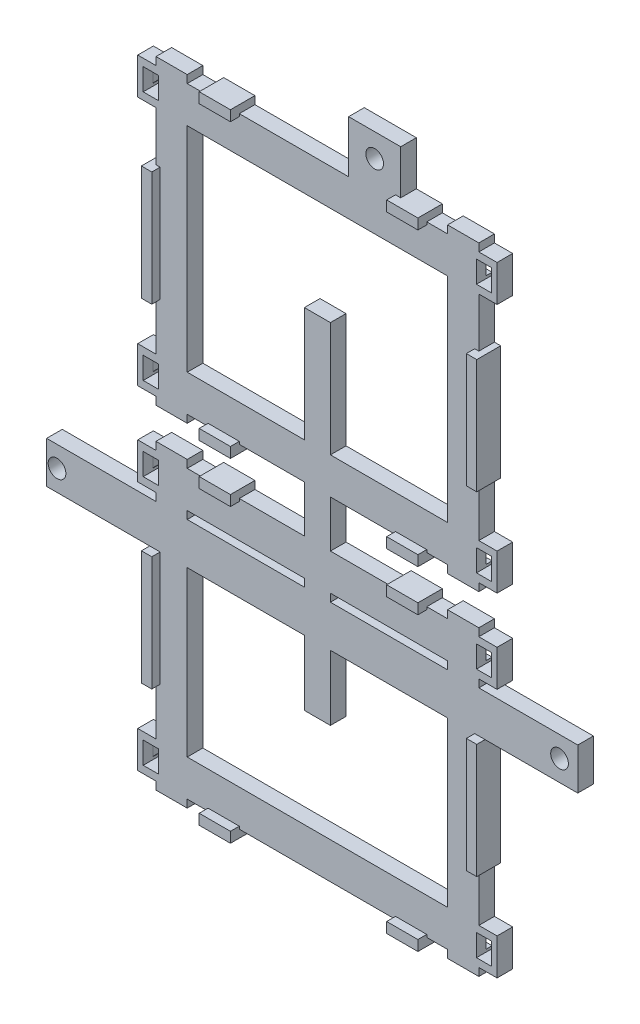
SolidWorks part; units mm, degrees
ref_plane "前视基准面" through (0, 0, 0) normal (0, 0, 1) x (1, 0, 0)
ref_plane "上视基准面" through (0, 0, 0) normal (0, 1, 0) x (1, 0, 0)
ref_plane "右视基准面" through (0, 0, 0) normal (1, 0, 0) x (0, 0, -1)
other "Configuration Table"
sketch "Sketch_Connected_support_rails" plane through (0, 0, 0) normal (0, 0, 1) x (1, 0, 0)
  line L0 (-25, -59.5) -> (-25, -61)
  line L1 (-25, -61) -> (-31, -61)
  line L2 (-31, -61) -> (-31, -59.5)
  line L3 (-31, -59.5) -> (-34.5, -59.5)
  line L4 (-34.5, -59.5) -> (-34.5, -52.5)
  line L5 (-34.5, -52.5) -> (-31, -52.5)
  line L6 (-31, -52.5) -> (-31, -43)
  line L7 (-31, -43) -> (-32.2, -43)
  line L8 (-32.2, -43) -> (-32.2, -21)
  line L9 (-32.2, -21) -> (-52, -21)
  line L10 (-52, -21) -> (-52, -13)
  line L11 (-52, -13) -> (-31, -13)
  line L12 (-31, -13) -> (-31, -11.5)
  line L13 (-31, -11.5) -> (-34.5, -11.5)
  line L14 (-34.5, -11.5) -> (-34.5, -4.5)
  line L15 (-34.5, -4.5) -> (-31, -4.5)
  line L16 (-31, -4.5) -> (-31, -3)
  line L17 (-31, -3) -> (-25, -3)
  line L18 (-25, -3) -> (-25, -4.5)
  line L19 (-25, -4.5) -> (-21, -4.5)
  line L20 (-21, -4.5) -> (-21, -3)
  line L21 (-21, -3) -> (-15, -3)
  line L22 (-15, -3) -> (-15, -4.5)
  line L23 (-15, -4.5) -> (-2.5, -4.5)
  line L24 (-2.5, -4.5) -> (-2.5, 4.5)
  line L25 (-2.5, 4.5) -> (-15, 4.5)
  line L26 (-15, 4.5) -> (-15, 3)
  line L27 (-15, 3) -> (-21, 3)
  line L28 (-21, 3) -> (-21, 4.5)
  line L29 (-21, 4.5) -> (-25, 4.5)
  line L30 (-25, 4.5) -> (-25, 3)
  line L31 (-25, 3) -> (-31, 3)
  line L32 (-31, 3) -> (-31, 4.5)
  line L33 (-31, 4.5) -> (-34.5, 4.5)
  line L34 (-34.5, 4.5) -> (-34.5, 11.5)
  line L35 (-34.5, 11.5) -> (-31, 11.5)
  line L36 (-31, 11.5) -> (-31, 21)
  line L37 (-31, 21) -> (-32.2, 21)
  line L38 (-32.2, 21) -> (-32.2, 43)
  line L39 (-32.2, 43) -> (-31, 43)
  line L40 (-31, 43) -> (-31, 52.5)
  line L41 (-31, 52.5) -> (-34.5, 52.5)
  line L42 (-34.5, 52.5) -> (-34.5, 59.5)
  line L43 (-34.5, 59.5) -> (-31, 59.5)
  line L44 (-31, 59.5) -> (-31, 61)
  line L45 (-31, 61) -> (-25, 61)
  line L46 (-25, 61) -> (-25, 59.5)
  line L47 (-25, 59.5) -> (-21, 59.5)
  line L48 (-21, 59.5) -> (-21, 61)
  line L49 (-21, 61) -> (-15, 61)
  line L50 (-15, 61) -> (-15, 59.5)
  line L51 (-15, 59.5) -> (6, 59.5)
  line L52 (6, 59.5) -> (6, 69.5)
  line L53 (6, 69.5) -> (16, 69.5)
  line L54 (16, 69.5) -> (16, 61)
  line L55 (16, 61) -> (21, 61)
  line L56 (21, 61) -> (21, 59.5)
  line L57 (21, 59.5) -> (25, 59.5)
  line L58 (25, 59.5) -> (25, 61)
  line L59 (25, 61) -> (31, 61)
  line L60 (31, 61) -> (31, 59.5)
  line L61 (31, 59.5) -> (34.5, 59.5)
  line L62 (34.5, 59.5) -> (34.5, 52.5)
  line L63 (34.5, 52.5) -> (31, 52.5)
  line L64 (31, 52.5) -> (31, 43)
  line L65 (31, 43) -> (32.2, 43)
  line L66 (32.2, 43) -> (32.2, 21)
  line L67 (32.2, 21) -> (31, 21)
  line L68 (31, 21) -> (31, 11.5)
  line L69 (31, 11.5) -> (34.5, 11.5)
  line L70 (34.5, 11.5) -> (34.5, 4.5)
  line L71 (34.5, 4.5) -> (31, 4.5)
  line L72 (31, 4.5) -> (31, 3)
  line L73 (31, 3) -> (25, 3)
  line L74 (25, 3) -> (25, 4.5)
  line L75 (25, 4.5) -> (21, 4.5)
  line L76 (21, 4.5) -> (21, 3)
  line L77 (21, 3) -> (15, 3)
  line L78 (15, 3) -> (15, 4.5)
  line L79 (15, 4.5) -> (2.5, 4.5)
  line L80 (2.5, 4.5) -> (2.5, -4.5)
  line L81 (2.5, -4.5) -> (15, -4.5)
  line L82 (15, -4.5) -> (15, -3)
  line L83 (15, -3) -> (21, -3)
  line L84 (21, -3) -> (21, -4.5)
  line L85 (21, -4.5) -> (25, -4.5)
  line L86 (25, -4.5) -> (25, -3)
  line L87 (25, -3) -> (31, -3)
  line L88 (31, -3) -> (31, -4.5)
  line L89 (31, -4.5) -> (34.5, -4.5)
  line L90 (34.5, -4.5) -> (34.5, -11.5)
  line L91 (34.5, -11.5) -> (31, -11.5)
  line L92 (31, -11.5) -> (31, -13)
  line L93 (31, -13) -> (50, -13)
  line L94 (50, -13) -> (50, -21)
  line L95 (50, -21) -> (32.2, -21)
  line L96 (32.2, -21) -> (32.2, -43)
  line L97 (32.2, -43) -> (31, -43)
  line L98 (31, -43) -> (31, -52.5)
  line L99 (31, -52.5) -> (34.5, -52.5)
  line L100 (34.5, -52.5) -> (34.5, -59.5)
  line L101 (34.5, -59.5) -> (31, -59.5)
  line L102 (31, -59.5) -> (31, -61)
  line L103 (31, -61) -> (25, -61)
  line L104 (25, -61) -> (25, -59.5)
  line L105 (25, -59.5) -> (21, -59.5)
  line L106 (21, -59.5) -> (21, -61)
  line L107 (21, -61) -> (15, -61)
  line L108 (15, -61) -> (15, -59.5)
  line L109 (15, -59.5) -> (-15, -59.5)
  line L110 (-15, -59.5) -> (-15, -61)
  line L111 (-15, -61) -> (-21, -61)
  line L112 (-21, -61) -> (-21, -59.5)
  line L113 (-21, -59.5) -> (-25, -59.5)
  line L114 (2.5, -11.5) -> (2.5, -13)
  line L115 (2.5, -13) -> (25, -13)
  line L116 (25, -13) -> (25, -11.5)
  line L117 (25, -11.5) -> (2.5, -11.5)
  line L118 (-25, -11.5) -> (-25, -13)
  line L119 (-25, -13) -> (-2.5, -13)
  line L120 (-2.5, -13) -> (-2.5, -11.5)
  line L121 (-2.5, -11.5) -> (-25, -11.5)
  line L122 (2.5, -21) -> (2.5, -33.5)
  line L123 (2.5, -33.5) -> (-2.5, -33.5)
  line L124 (-2.5, -33.5) -> (-2.5, -21)
  line L125 (-2.5, -21) -> (-25, -21)
  line L126 (-25, -21) -> (-25, -52.5)
  line L127 (-25, -52.5) -> (25, -52.5)
  line L128 (25, -52.5) -> (25, -21)
  line L129 (25, -21) -> (2.5, -21)
  line L130 (-25, 11.5) -> (-2.5, 11.5)
  line L131 (-2.5, 11.5) -> (-2.5, 33.5)
  line L132 (-2.5, 33.5) -> (2.5, 33.5)
  line L133 (2.5, 33.5) -> (2.5, 11.5)
  line L134 (2.5, 11.5) -> (25, 11.5)
  line L135 (25, 11.5) -> (25, 52.5)
  line L136 (25, 52.5) -> (-25, 52.5)
  line L137 (-25, 52.5) -> (-25, 11.5)
extrude "Connected_support_rails" add sketch "Sketch_Connected_support_rails" along normal blind 3 from offset 0
sketch "Sketch_Side_stops" plane through (0, 0, 0) normal (0, 0, 1) x (1, 0, 0)
  line L0 (-32.2, -21) -> (-30.2, -21)
  line L1 (-30.2, -21) -> (-30.2, -43)
  line L2 (-30.2, -43) -> (-32.2, -43)
  line L3 (-32.2, -43) -> (-32.2, -21)
  line L4 (30.2, -21) -> (32.2, -21)
  line L5 (32.2, -21) -> (32.2, -43)
  line L6 (32.2, -43) -> (30.2, -43)
  line L7 (30.2, -43) -> (30.2, -21)
  line L8 (-32.2, 43) -> (-30.2, 43)
  line L9 (-30.2, 43) -> (-30.2, 21)
  line L10 (-30.2, 21) -> (-32.2, 21)
  line L11 (-32.2, 21) -> (-32.2, 43)
  line L12 (30.2, 43) -> (32.2, 43)
  line L13 (32.2, 43) -> (32.2, 21)
  line L14 (32.2, 21) -> (30.2, 21)
  line L15 (30.2, 21) -> (30.2, 43)
extrude "Side_stops" add sketch "Sketch_Side_stops" along normal blind 1.6 from offset 3
sketch "Sketch_End_stops" plane through (0, 0, 0) normal (0, 0, 1) x (1, 0, 0)
  line L0 (-15, -59) -> (-15, -61)
  line L1 (-15, -61) -> (-21, -61)
  line L2 (-21, -61) -> (-21, -59)
  line L3 (-21, -59) -> (-15, -59)
  line L4 (21, -59) -> (21, -61)
  line L5 (21, -61) -> (15, -61)
  line L6 (15, -61) -> (15, -59)
  line L7 (15, -59) -> (21, -59)
  line L8 (-15, -3) -> (-15, -5)
  line L9 (-15, -5) -> (-21, -5)
  line L10 (-21, -5) -> (-21, -3)
  line L11 (-21, -3) -> (-15, -3)
  line L12 (21, -3) -> (21, -5)
  line L13 (21, -5) -> (15, -5)
  line L14 (15, -5) -> (15, -3)
  line L15 (15, -3) -> (21, -3)
  line L16 (-15, 5) -> (-15, 3)
  line L17 (-15, 3) -> (-21, 3)
  line L18 (-21, 3) -> (-21, 5)
  line L19 (-21, 5) -> (-15, 5)
  line L20 (21, 5) -> (21, 3)
  line L21 (21, 3) -> (15, 3)
  line L22 (15, 3) -> (15, 5)
  line L23 (15, 5) -> (21, 5)
  line L24 (-15, 61) -> (-15, 59)
  line L25 (-15, 59) -> (-21, 59)
  line L26 (-21, 59) -> (-21, 61)
  line L27 (-21, 61) -> (-15, 61)
  line L28 (21, 61) -> (21, 59)
  line L29 (21, 59) -> (15, 59)
  line L30 (15, 59) -> (15, 61)
  line L31 (15, 61) -> (21, 61)
extrude "End_stops" add sketch "Sketch_End_stops" along normal blind 1.7 from offset 3
sketch "Sketch_Strap_passages" plane through (0, 0, 0) normal (0, 0, 1) x (1, 0, 0)
  line L0 (-30.55, -53.9) -> (-30.55, -58.1)
  line L1 (-30.55, -58.1) -> (-33.45, -58.1)
  line L2 (-33.45, -58.1) -> (-33.45, -53.9)
  line L3 (-33.45, -53.9) -> (-30.55, -53.9)
  line L4 (33.45, -53.9) -> (33.45, -58.1)
  line L5 (33.45, -58.1) -> (30.55, -58.1)
  line L6 (30.55, -58.1) -> (30.55, -53.9)
  line L7 (30.55, -53.9) -> (33.45, -53.9)
  line L8 (-30.55, -5.9) -> (-30.55, -10.1)
  line L9 (-30.55, -10.1) -> (-33.45, -10.1)
  line L10 (-33.45, -10.1) -> (-33.45, -5.9)
  line L11 (-33.45, -5.9) -> (-30.55, -5.9)
  line L12 (33.45, -5.9) -> (33.45, -10.1)
  line L13 (33.45, -10.1) -> (30.55, -10.1)
  line L14 (30.55, -10.1) -> (30.55, -5.9)
  line L15 (30.55, -5.9) -> (33.45, -5.9)
  line L16 (-30.55, 10.1) -> (-30.55, 5.9)
  line L17 (-30.55, 5.9) -> (-33.45, 5.9)
  line L18 (-33.45, 5.9) -> (-33.45, 10.1)
  line L19 (-33.45, 10.1) -> (-30.55, 10.1)
  line L20 (33.45, 10.1) -> (33.45, 5.9)
  line L21 (33.45, 5.9) -> (30.55, 5.9)
  line L22 (30.55, 5.9) -> (30.55, 10.1)
  line L23 (30.55, 10.1) -> (33.45, 10.1)
  line L24 (-30.55, 58.1) -> (-30.55, 53.9)
  line L25 (-30.55, 53.9) -> (-33.45, 53.9)
  line L26 (-33.45, 53.9) -> (-33.45, 58.1)
  line L27 (-33.45, 58.1) -> (-30.55, 58.1)
  line L28 (33.45, 58.1) -> (33.45, 53.9)
  line L29 (33.45, 53.9) -> (30.55, 53.9)
  line L30 (30.55, 53.9) -> (30.55, 58.1)
  line L31 (30.55, 58.1) -> (33.45, 58.1)
extrude "Strap_passages" cut sketch "Sketch_Strap_passages" along normal blind 5 from offset 1
sketch "Sketch_Floor_M3" plane through (0, 0, 0) normal (0, 0, 1) x (1, 0, 0)
  circle A0 centre (-50, -17) radius 1.7
  circle A1 centre (46.5, -17) radius 1.7
  circle A2 centre (11, 65) radius 1.7
  dimension "D1" = 3.4
  dimension "D2" = 3.4
  dimension "D3" = 3.4
extrude "Floor_M3" cut sketch "Sketch_Floor_M3" along normal blind 6 from offset 1
sketch "Sketch_Under_strap_recess" plane through (0, 0, 0) normal (0, 0, 1) x (1, 0, 0)
  line L0 (-33.5, -54.4) -> (33.5, -54.4)
  line L1 (33.5, -54.4) -> (33.5, -57.6)
  line L2 (33.5, -57.6) -> (-33.5, -57.6)
  line L3 (-33.5, -57.6) -> (-33.5, -54.4)
  line L4 (-33.5, -6.4) -> (33.5, -6.4)
  line L5 (33.5, -6.4) -> (33.5, -9.6)
  line L6 (33.5, -9.6) -> (-33.5, -9.6)
  line L7 (-33.5, -9.6) -> (-33.5, -6.4)
  line L8 (-33.5, 9.6) -> (33.5, 9.6)
  line L9 (33.5, 9.6) -> (33.5, 6.4)
  line L10 (33.5, 6.4) -> (-33.5, 6.4)
  line L11 (-33.5, 6.4) -> (-33.5, 9.6)
  line L12 (-33.5, 57.6) -> (33.5, 57.6)
  line L13 (33.5, 57.6) -> (33.5, 54.4)
  line L14 (33.5, 54.4) -> (-33.5, 54.4)
  line L15 (-33.5, 54.4) -> (-33.5, 57.6)
extrude "Under_strap_recess" cut sketch "Sketch_Under_strap_recess" along normal blind 1.3 from offset 0.15
